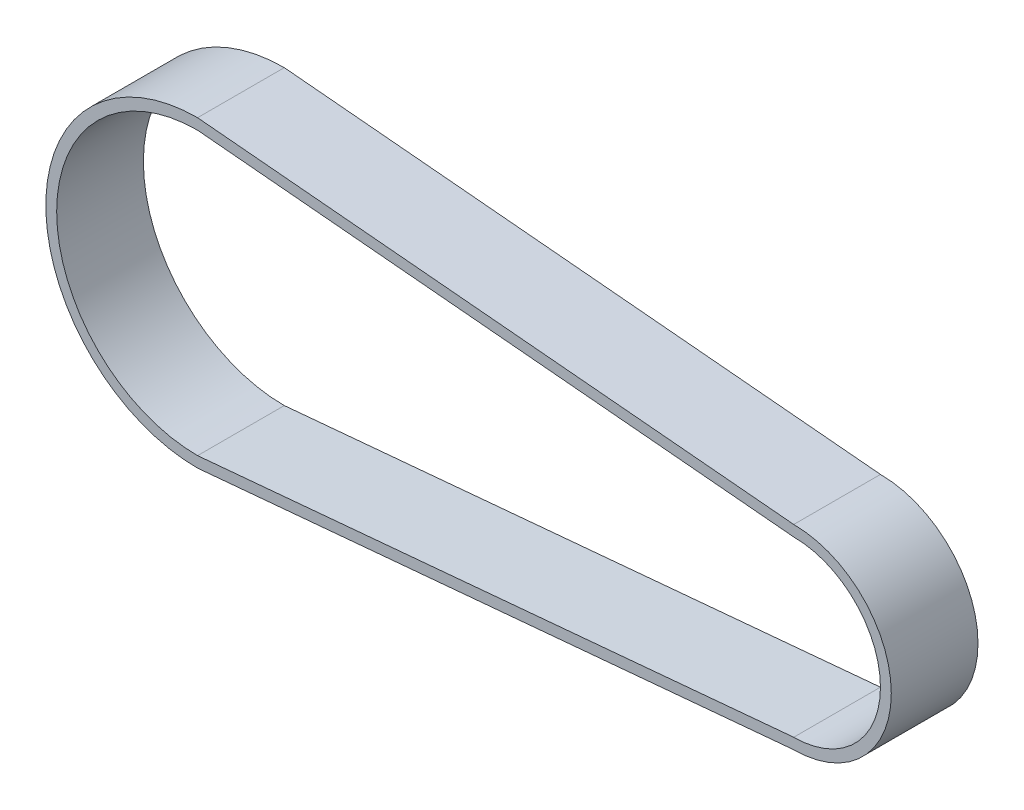
SolidWorks part; units mm, degrees
ref_plane "Plan de face" through (0, 0, 0) normal (0, 0, 1) x (1, 0, 0)
ref_plane "Plan de dessus" through (0, 0, 0) normal (0, 1, 0) x (1, 0, 0)
ref_plane "Plan de droite" through (0, 0, 0) normal (1, 0, 0) x (0, 0, -1)
sketch "Esquisse1" plane through (0, 0, 0) normal (0, 0, 1) x (1, 0, 0)
  line L0 (0, 0) -> (25, 0) construction
  line L1 (0, 0) -> (-30, 0) construction
  line L20 (-30, -13) -> (25, -8)
  line L21 (-30, 13) -> (25, 8)
  line L22 (-30, 14) -> (25, 9)
  line L23 (-30, -14) -> (25, -9)
  circle A0 centre (-30, 0) radius 13 construction
  circle A1 centre (25, 0) radius 8 construction
  circle A2 centre (25, 0) radius 9 construction
  circle A3 centre (-30, 0) radius 14 construction
  arc A4 (-30, 14) -> (-30, -14) centre (-30, 0) ccw
  arc A5 (-30, 13) -> (-30, -13) centre (-30, 0) ccw
  arc A6 (25, 8) -> (25, -8) centre (25, 0) cw
  arc A7 (25, -9) -> (25, 9) centre (25, 0) ccw
extrude "Boss.-Extru.1" add sketch "Esquisse1" along normal blind 8
